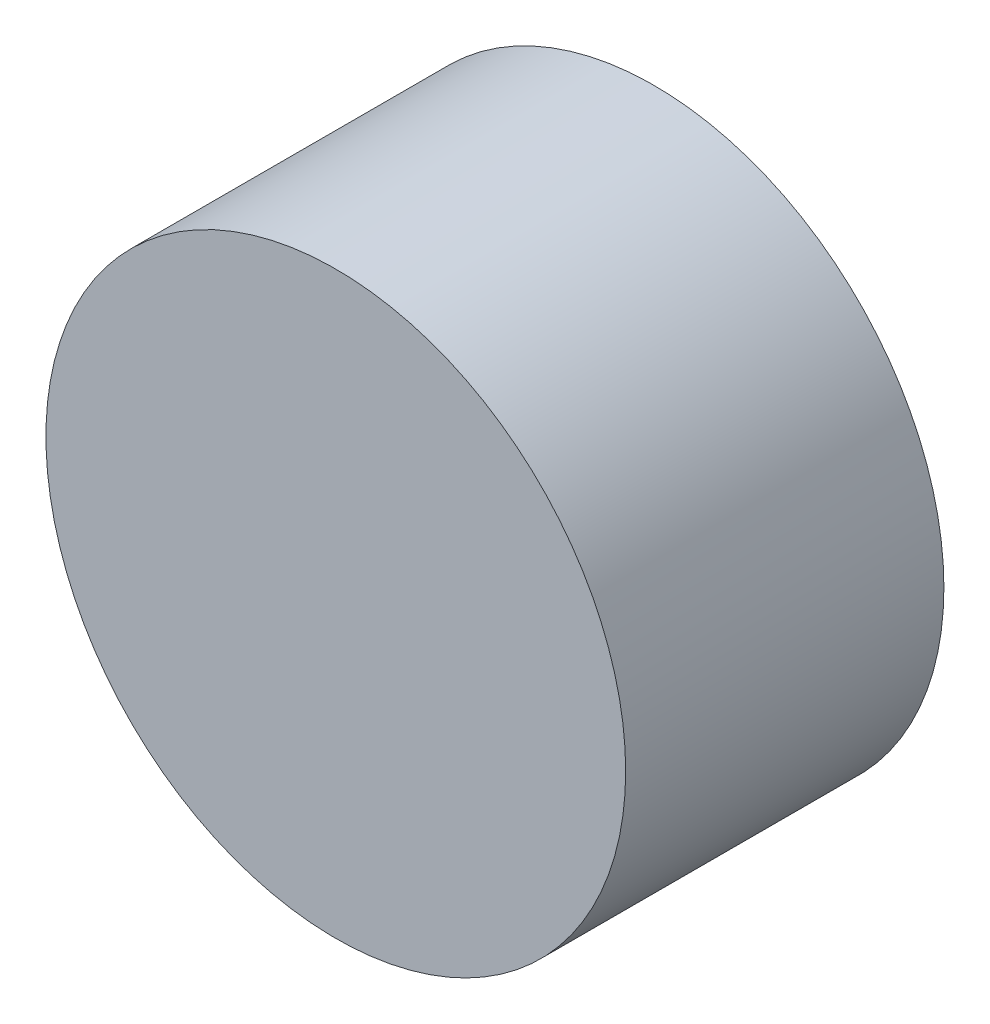
SolidWorks part; units mm, degrees
material "Kurşunlu Ticari Bronz"
ref_plane "Ön Düzlem" through (0, 0, 0) normal (0, 0, 1) x (1, 0, 0)
ref_plane "Üst Düzlem" through (0, 0, 0) normal (0, 1, 0) x (1, 0, 0)
ref_plane "Sağ Düzlem" through (0, 0, 0) normal (1, 0, 0) x (0, 0, -1)
sketch "Çizim1" plane through (0, 0, 0) normal (0, 0, 1) x (1, 0, 0)
  circle A0 centre (0, 0) radius 2.25
  dimension "D1" = 4.5
extrude "Yükseklik-Ekstrüzyon1" add sketch "Çizim1" along normal blind 2.47
